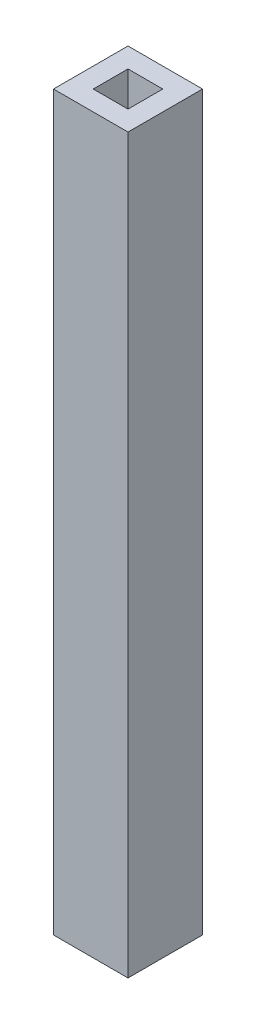
SolidWorks part; units mm, degrees
ref_plane "Front Plane" through (0, 0, 0) normal (0, 0, 1) x (1, 0, 0)
ref_plane "Top Plane" through (0, 0, 0) normal (0, 1, 0) x (1, 0, 0)
ref_plane "Right Plane" through (0, 0, 0) normal (1, 0, 0) x (0, 0, -1)
sketch "Sketch2" plane through (0, 0, 0) normal (0, 1, 0) x (1, 0, 0)
  line L1 (-63.3931, -106.2479) -> (-44.3431, -106.2479)
  line L2 (-63.3931, -106.2479) -> (-63.3931, -125.2979)
  line L3 (-63.3931, -125.2979) -> (-44.3431, -125.2979)
  line L4 (-44.3431, -106.2479) -> (-44.3431, -125.2979)
  line L5 (-58.3131, -111.3279) -> (-49.4231, -111.3279)
  line L6 (-58.3131, -111.3279) -> (-58.3131, -120.2179)
  line L7 (-58.3131, -120.2179) -> (-49.4231, -120.2179)
  line L8 (-49.4231, -111.3279) -> (-49.4231, -120.2179)
  dimension "D1" = 19.05
  dimension "D2" = 19.05
  dimension "D3" = 5.08
  dimension "D4" = 5.08
  dimension "D5" = 5.08
  dimension "D6" = 5.08
extrude "Boss-Extrude1" add sketch "Sketch2" along normal blind 187.325
